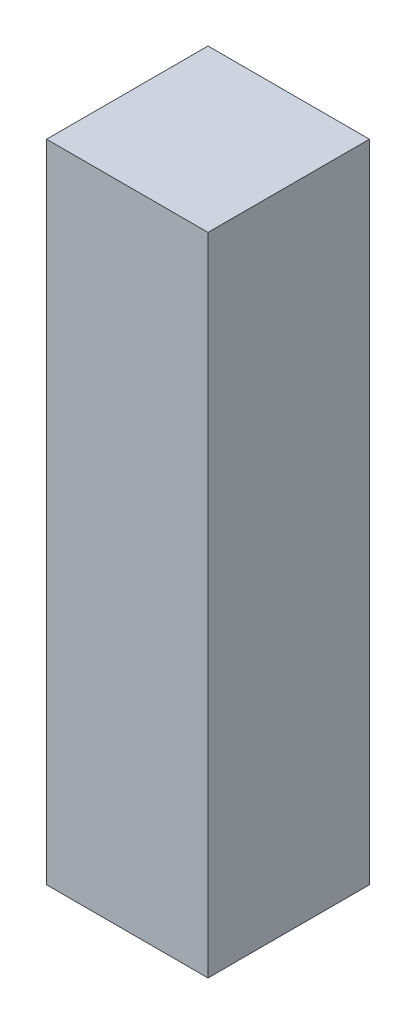
SolidWorks part; units mm, degrees
ref_plane "Front Plane" through (0, 0, 0) normal (0, 0, 1) x (1, 0, 0)
ref_plane "Top Plane" through (0, 0, 0) normal (0, 1, 0) x (1, 0, 0)
ref_plane "Right Plane" through (0, 0, 0) normal (1, 0, 0) x (0, 0, -1)
sketch "Sketch2" plane through (0, 0, 0) normal (0, 1, 0) x (1, 0, 0)
  line L1 (-12.5, -12.5) -> (12.5, -12.5)
  line L2 (-12.5, -12.5) -> (-12.5, 12.5)
  line L3 (-12.5, 12.5) -> (12.5, 12.5)
  line L4 (12.5, -12.5) -> (12.5, 12.5)
  line L5 (-12.5, -12.5) -> (12.5, 12.5) construction
  line L6 (-12.5, 12.5) -> (12.5, -12.5) construction
  point P0 (0, 0)
  dimension "D1" = 25
  dimension "D2" = 25
extrude "Boss-Extrude2" add sketch "Sketch2" along normal blind 100 contours L2 L1 L4 L3
shell "Shell2" thickness 3
move or copy body "Body-Move/Copy1" bodies to move or copy 102 copy no rotation origin (0, 50, 0) rotation axis (0, 0, 1) rotation angle 180
